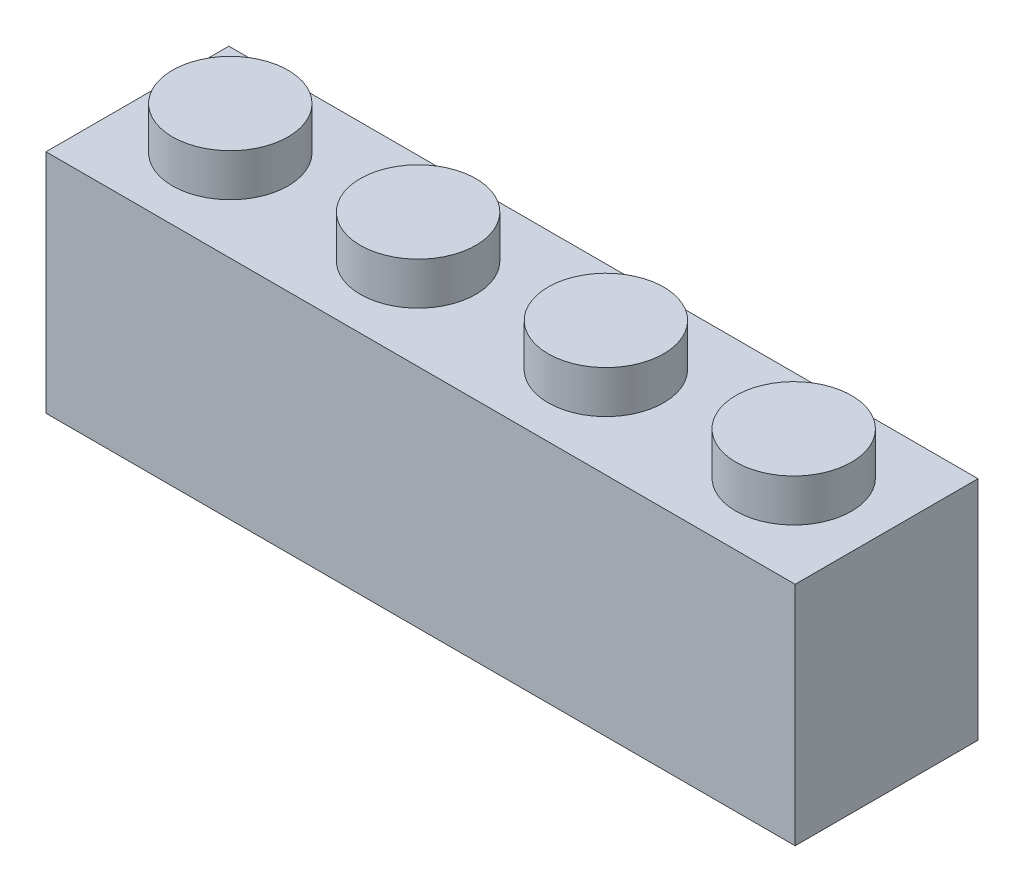
SolidWorks part; units mm, degrees
ref_plane "Front Plane" through (0, 0, 0) normal (0, 0, 1) x (1, 0, 0)
ref_plane "Top Plane" through (0, 0, 0) normal (0, 1, 0) x (1, 0, 0)
ref_plane "Right Plane" through (0, 0, 0) normal (1, 0, 0) x (0, 0, -1)
sketch "Sketch1" plane through (0, 0, 0) normal (0, 1, 0) x (1, 0, 0)
  line L1 (-15.875, 3.875) -> (15.875, 3.875)
  line L2 (-15.875, 3.875) -> (-15.875, -3.875)
  line L3 (-15.875, -3.875) -> (15.875, -3.875)
  line L4 (15.875, 3.875) -> (15.875, -3.875)
  line L5 (-15.875, 3.875) -> (15.875, -3.875) construction
  line L6 (-15.875, -3.875) -> (15.875, 3.875) construction
  point P0 (0, 0)
  dimension "D1" = 7.75
  dimension "D2" = 31.75
extrude "Boss-Extrude1" add sketch "Sketch1" against normal blind 9.6
sketch "Sketch2" plane through (0, 0, 0) normal (0, 1, 0) x (1, 0, 0)
  line L1 (-15.875, 3.875) -> (-15.875, -3.875) construction
  line L5 (15.875, 3.875) -> (-15.875, 3.875) construction
  circle A0 centre (-11.94, 0) radius 2.45
  circle A1 centre (-3.98, 0) radius 2.45
  circle A2 centre (3.98, 0) radius 2.45
  circle A3 centre (11.94, 0) radius 2.45
  dimension "D2" = 3.935
  dimension "D3" = 4.9
  dimension "D4" = 3.875
  dimension "D5" = 7.96
  dimension "D1" = 4
extrude "Boss-Extrude2" add sketch "Sketch2" along normal blind 1.8
shell "Shell1" thickness 1.5
